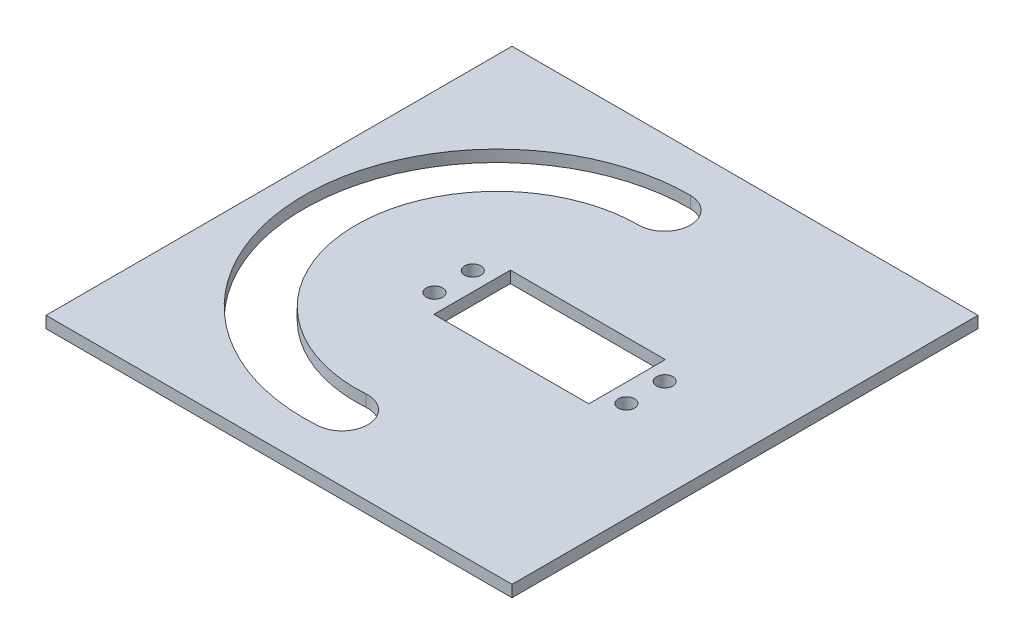
SolidWorks part; units mm, degrees
ref_plane "Front Plane" through (0, 0, 0) normal (0, 0, 1) x (1, 0, 0)
ref_plane "Top Plane" through (0, 0, 0) normal (0, 1, 0) x (1, 0, 0)
ref_plane "Right Plane" through (0, 0, 0) normal (1, 0, 0) x (0, 0, -1)
sketch "Sketch1" plane through (0, 0, 0) normal (0, 1, 0) x (1, 0, 0)
  line L1 (-70, -80) -> (70, -80)
  line L2 (-70, -80) -> (-70, 80)
  line L3 (-70, 80) -> (70, 80)
  line L4 (70, -80) -> (70, 80)
  line L5 (-70, -80) -> (70, 80) construction
  line L6 (-70, 80) -> (70, -80) construction
  point P0 (0, 0)
  dimension "D1" = 140
  dimension "D2" = 160
extrude "Boss-Extrude1" add sketch "Sketch1" along normal blind 3
sketch "Sketch2" plane through (0, 3, 0) normal (0, 1, 0) x (1, 0, 0)
  line L1 (-58.5, -58.5) -> (58.5, -58.5)
  line L2 (-58.5, -58.5) -> (-58.5, 58.5)
  line L3 (-58.5, 58.5) -> (58.5, 58.5)
  line L4 (58.5, -58.5) -> (58.5, 58.5)
  line L5 (-58.5, -58.5) -> (58.5, 58.5) construction
  line L6 (-58.5, 58.5) -> (58.5, -58.5) construction
  line L7 (60, -60) -> (-60, -60)
  line L8 (60, -60) -> (60, 60)
  line L9 (60, 60) -> (-60, 60)
  line L10 (-60, -60) -> (-60, 60)
  line L11 (60, -60) -> (-60, 60) construction
  line L12 (60, 60) -> (-60, -60) construction
  point P0 (0, 0)
  point P6 (0, 0)
  dimension "D1" = 117
  dimension "D2" = 117
  dimension "D3" = 120
extrude "Boss-Extrude2" add sketch "Sketch2" along normal blind 70
sketch "Sketch4" plane through (0, 73, 0) normal (0, 1, 0) x (1, 0, 0)
  line L1 (-60, 60) -> (60, 60)
  line L2 (-60, 60) -> (-60, -60)
  line L3 (-60, -60) -> (60, -60)
  line L4 (60, 60) -> (60, -60)
  dimension "D1" = 120
  dimension "D2" = 120
extrude "Boss-Extrude4" add sketch "Sketch4" along normal blind 3
sketch "Sketch5" plane through (0, 76, 0) normal (0, 1, 0) x (1, 0, 0)
  line L0 (-60, 60) -> (60, -60) construction
  line L1 (-10.27, -9.855) -> (29.63, -9.855)
  line L2 (-10.27, -9.855) -> (-10.27, 9.855)
  line L3 (-10.27, 9.855) -> (29.63, 9.855)
  line L4 (29.63, -9.855) -> (29.63, 9.855)
  line L5 (-10.27, -9.855) -> (29.63, 9.855) construction
  line L6 (-10.27, 9.855) -> (29.63, -9.855) construction
  line L7 (60, -60) -> (60, 60) construction
  line L8 (60, -60) -> (60, 60) construction
  line L9 (60, -60) -> (60, 60) construction
  line L10 (60, 60) -> (-60, 60) construction
  line L11 (60, 60) -> (-60, -60) construction
  circle A1 centre (34.39, -4.925) radius 2.1
  circle A2 centre (34.39, 4.925) radius 2.1
  circle A4 centre (-15.03, -4.925) radius 2.1
  circle A5 centre (-15.03, 4.925) radius 2.1
  point P3 (9.68, 0)
  dimension "D2" = 4.2
  dimension "D6" = 9.85
  dimension "D7" = 4.93
  dimension "D8" = 4.93
  dimension "D9" = 4.93
  dimension "D10" = 9.68
  dimension "D11" = 4.93
  dimension "D12" = 4.93
  dimension "D1" = 39.9
  dimension "D3" = 19.71
  dimension "D4" = 4.76
  dimension "D5" = 4.76
extrude "Cut-Extrude2" cut sketch "Sketch5" against normal blind 3
sketch "Sketch6" plane through (0, 76, 0) normal (0, 1, 0) x (1, 0, 0)
  line L1 (9.1491, -8.655) -> (-9.1491, -8.655)
  line L2 (9.1491, -8.655) -> (9.1491, 8.655)
  line L3 (9.1491, 8.655) -> (-9.1491, 8.655)
  line L4 (-9.1491, -8.655) -> (-9.1491, 8.655)
  line L5 (9.1491, -8.655) -> (-9.1491, 8.655) construction
  line L6 (9.1491, 8.655) -> (-9.1491, -8.655) construction
  point P0 (0, 0)
extrude "Cut-Extrude3" cut sketch "Sketch6" against normal blind 3
sketch "Sketch13" plane through (0, 76, 0) normal (0, 1, 0) x (1, 0, 0)
  arc A0 (-3.7926, 43.0768) -> (-0.8101, -42.9734) centre (-3.7926, 0) ccw construction
  arc A1 (-3.7926, 49.7288) -> (-0.3495, -49.6094) centre (-3.7926, 0) ccw
  arc A2 (-3.7926, 36.4249) -> (-1.2706, -36.3375) centre (-3.7926, 0) ccw
  arc A3 (-3.7926, 36.4249) -> (-3.7926, 49.7288) centre (-3.7926, 43.0768) ccw
  arc A4 (-0.3495, -49.6094) -> (-1.2706, -36.3375) centre (-0.8101, -42.9734) ccw
  point P3 (-46.8436, -1.4922)
extrude "Cut-Extrude8" cut sketch "Sketch13" against normal blind 5
sketch "Sketch15" plane through (0, 3, 0) normal (0, 1, 0) x (1, 0, 0)
  line L0 (70, 80) -> (-70, 80) construction
  line L1 (90, 80) -> (-169.0216, 80)
  line L2 (90, 80) -> (90, -100.2694)
  line L3 (90, -100.2694) -> (-169.0216, -100.2694)
  line L4 (-169.0216, 80) -> (-169.0216, -100.2694)
extrude "Boss-Extrude5" add sketch "Sketch15" against normal blind 3
sketch "Sketch18" plane through (0, 3, 0) normal (0, 1, 0) x (1, 0, 0)
  circle A0 centre (-55.452, -27.2274) radius 1.6 construction
  circle A1 centre (-55.452, -27.2274) radius 1.6
  circle A2 centre (-55.452, 32.2086) radius 1.6 construction
  circle A3 centre (-55.452, 32.2086) radius 1.6
  circle A4 centre (4.746, 32.2086) radius 1.6 construction
  circle A5 centre (4.746, 32.2086) radius 1.6
  circle A6 centre (4.746, -27.2274) radius 1.6 construction
  circle A7 centre (4.746, -27.2274) radius 1.6
extrude "Cut-Extrude9" cut sketch "Sketch18" against normal blind 10
sketch "Sketch19" plane through (-60, 0, 0) normal (-1, 0, 0) x (0, 0, 1)
  line L0 (12.3674, 3) -> (12.3674, 33) construction
  line L1 (-60, 3) -> (60, 3) construction
  line L2 (-5.6466, 31.35) -> (-5.6466, 26.9) construction
  line L3 (6.3674, 30.75) -> (18.3674, 30.75)
  line L4 (6.3674, 30.75) -> (6.3674, 35.25)
  line L5 (6.3674, 35.25) -> (18.3674, 35.25)
  line L6 (18.3674, 30.75) -> (18.3674, 35.25)
  line L7 (6.3674, 30.75) -> (18.3674, 35.25) construction
  line L8 (6.3674, 35.25) -> (18.3674, 30.75) construction
  line L9 (-5.2594, 33) -> (-5.2594, 41.4) construction
  line L10 (-5.2594, 33) -> (-17.2594, 33) construction
  line L11 (-5.2594, 41.4) -> (-17.2594, 41.4) construction
  line L12 (-17.2594, 33) -> (-17.2594, 41.4) construction
  line L13 (-33.6488, 33.0619) -> (-23.5648, 33.0619) construction
  line L14 (-28.1126, 38.85) -> (-28.1126, 27.45) construction
  line L15 (-23.5648, 40.424) -> (-23.5648, 33.0619) construction
  line L16 (-33.6488, 40.424) -> (-23.5648, 40.424) construction
  line L17 (-33.6488, 40.424) -> (-33.6488, 33.0619) construction
  line L18 (-5.2594, 33) -> (-5.2594, 41.4)
  line L19 (-5.2594, 33) -> (-17.2594, 33)
  line L20 (-5.2594, 41.4) -> (-17.2594, 41.4)
  line L21 (-17.2594, 33) -> (-17.2594, 41.4)
  line L22 (-33.6488, 33.0619) -> (-23.5648, 33.0619)
  line L23 (-28.1126, 38.85) -> (-28.1126, 27.45)
  line L24 (-23.5648, 40.424) -> (-23.5648, 33.0619)
  line L25 (-33.6488, 40.424) -> (-23.5648, 40.424)
  line L26 (-33.6488, 40.424) -> (-33.6488, 33.0619)
  dimension "D1" = 14.86
  dimension "D2" = 30
  dimension "D3" = 4.5
  dimension "D4" = 90
  dimension "D5" = 12
extrude "Cut-Extrude11" cut sketch "Sketch19" against normal blind 5
sketch "Sketch20" plane through (0, 0, 60) normal (0, 0, 1) x (1, 0, 0)
  line L0 (-60, 76) -> (60, 76) construction
  line L1 (-185.0713, 73) -> (113.7575, 73)
  line L2 (-185.0713, 73) -> (-185.0713, -17.2903)
  line L3 (-185.0713, -17.2903) -> (113.7575, -17.2903)
  line L4 (113.7575, 73) -> (113.7575, -17.2903)
  point P4 (113.7575, -18.7745)
  dimension "D1" = 3
extrude "Cut-Extrude12" cut sketch "Sketch20" against normal through all
sketch "Sketch21" plane through (0, 3, 0) normal (0, 1, 0) x (1, 0, 0)
  line L1 (-172.7034, -53.1648) -> (112.59, -53.1648)
  line L2 (-172.7034, -53.1648) -> (-172.7034, -161.0124)
  line L3 (-172.7034, -161.0124) -> (112.59, -161.0124)
  line L4 (112.59, -53.1648) -> (112.59, -161.0124)
extrude "Cut-Extrude13" cut sketch "Sketch21" against normal through all
